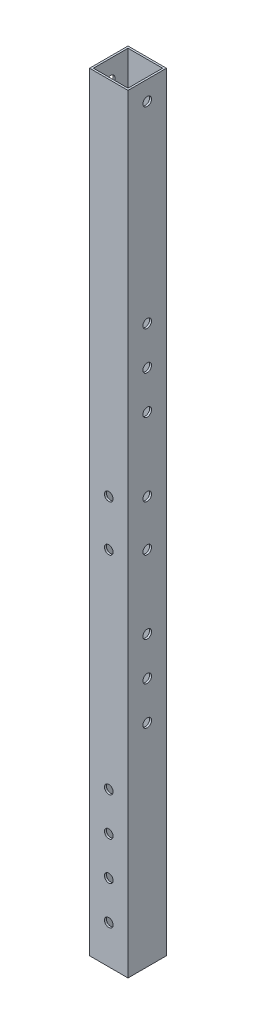
SolidWorks part; units mm, degrees
ref_plane "Front Plane" through (0, 0, 0) normal (0, 0, 1) x (1, 0, 0)
ref_plane "Top Plane" through (0, 0, 0) normal (0, 1, 0) x (1, 0, 0)
ref_plane "Right Plane" through (0, 0, 0) normal (1, 0, 0) x (0, 0, -1)
sketch "Sketch1" plane through (0, 0, 0) normal (0, 1, 0) x (1, 0, 0)
  line L0 (-9, -9) -> (-9, 9)
  line L5 (-10, -10) -> (10, -10)
  line L6 (-10, -10) -> (-10, 10)
  line L7 (-10, 10) -> (10, 10)
  line L8 (10, -10) -> (10, 10)
  line L9 (-10, -10) -> (10, 10) construction
  line L10 (-10, 10) -> (10, -10) construction
  line L11 (-9, 9) -> (9, 9)
  line L12 (9, -9) -> (9, 9)
  line L13 (-9, -9) -> (9, -9)
  point P0 (0, 0)
  dimension "D1" = 20
  dimension "D2" = 20
  dimension "D3" = 1
extrude "Boss-Extrude1" add sketch "Sketch1" along normal blind 400
sketch "Sketch4" plane through (0, 0, -10) normal (0, 0, -1) x (-1, 0, 0)
  line L0 (-10, 0) -> (10, 0) construction
  line L1 (-10, 200) -> (10, 200) construction
  line L2 (-10, 400) -> (-10, 0) construction
  line L3 (10, 400) -> (10, 0) construction
  circle A0 centre (0, 20) radius 2.25
  circle A1 centre (0, 40) radius 2.25
  circle A2 centre (0, 60) radius 2.25
  circle A3 centre (0, 80) radius 2.25
  circle A4 centre (0, 188) radius 2.25
  circle A5 centre (0, 212) radius 2.25
  dimension "D1" = 4.5
  dimension "D4" = 4.5
  dimension "D2" = 20
  dimension "D5" = 12
  dimension "D3" = 4
extrude "Cut-Extrude1" cut sketch "Sketch4" against normal through all
sketch "Sketch5" plane through (-10, 0, 0) normal (-1, 0, 0) x (0, 0, 1)
  line L0 (-10, 0) -> (10, 0) construction
  line L1 (0, 110) -> (0, 130) construction
  line L2 (10, 200) -> (-10, 200) construction
  line L3 (10, 400) -> (10, 0) construction
  line L4 (-10, 400) -> (-10, 0) construction
  line L5 (-10, 400) -> (10, 400) construction
  circle A0 centre (0, 188) radius 2.25
  circle A1 centre (0, 212) radius 2.25
  circle A2 centre (0, 110) radius 2.25
  circle A3 centre (0, 130) radius 2.25
  circle A4 centre (0, 150) radius 2.25
  circle A6 centre (0, 170) radius 2.25 [skipped]
  circle A7 centre (0, 250) radius 2.25
  circle A8 centre (0, 290) radius 2.25
  circle A9 centre (0, 270) radius 2.25
  circle A10 centre (0, 390) radius 2.25
  point P8 (0, 0)
  point P33 (0, 390)
  dimension "D1" = 4.5
  dimension "D2" = 12
  dimension "D3" = 12
  dimension "D4" = 4.5
  dimension "D5" = 110
  dimension "D7" = 20
  dimension "D8" = 10
  dimension "D6" = 4
extrude "Cut-Extrude2" cut sketch "Sketch5" against normal through all
